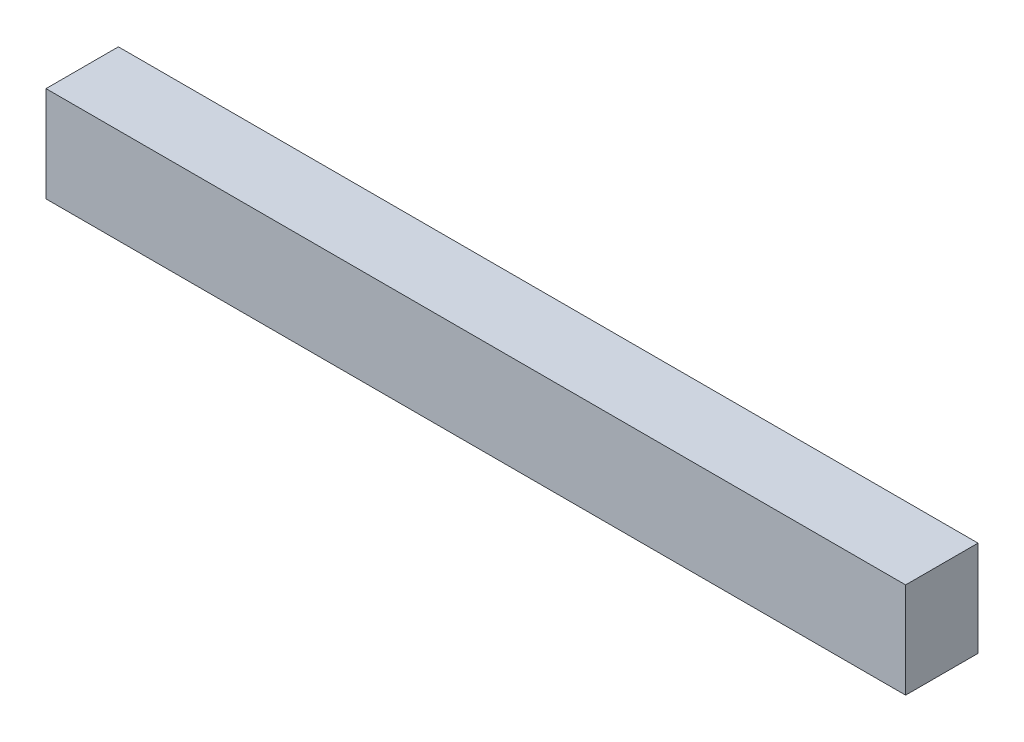
SolidWorks part; units mm, degrees
ref_plane "Front Plane" through (0, 0, 0) normal (0, 0, 1) x (1, 0, 0)
ref_plane "Top Plane" through (0, 0, 0) normal (0, 1, 0) x (1, 0, 0)
ref_plane "Right Plane" through (0, 0, 0) normal (1, 0, 0) x (0, 0, -1)
sketch "Sketch1" plane through (0, 0, 0) normal (0, 0, 1) x (1, 0, 0)
  line L1 (-10.8585, -1.2065) -> (10.8585, -1.2065)
  line L2 (-10.8585, -1.2065) -> (-10.8585, 1.2065)
  line L3 (-10.8585, 1.2065) -> (10.8585, 1.2065)
  line L4 (10.8585, -1.2065) -> (10.8585, 1.2065)
  line L5 (-10.8585, -1.2065) -> (10.8585, 1.2065) construction
  line L6 (-10.8585, 1.2065) -> (10.8585, -1.2065) construction
  point P0 (0, 0)
  dimension "D1" = 2.413
  dimension "D2" = 21.717
extrude "Boss-Extrude1" add sketch "Sketch1" along normal blind 1.8288
